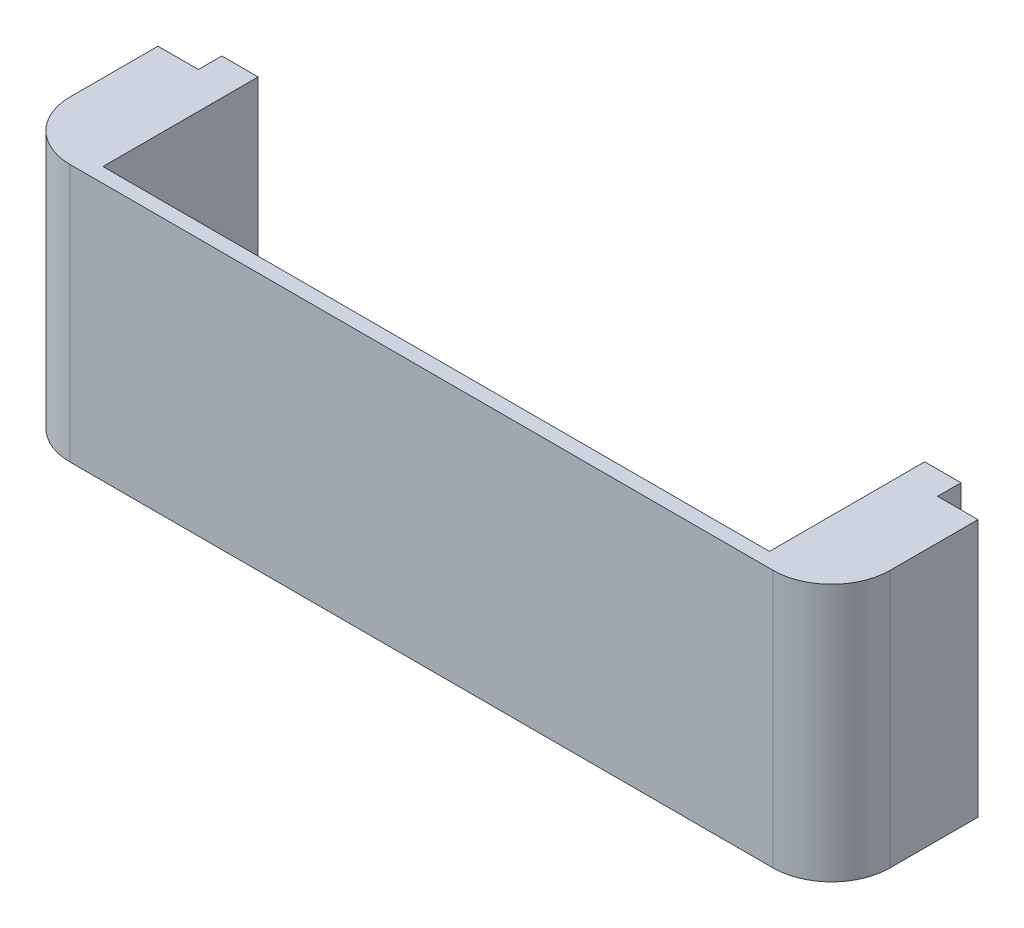
SolidWorks part; units mm, degrees
ref_plane "Front Plane" through (0, 0, 0) normal (0, 0, 1) x (1, 0, 0)
ref_plane "Top Plane" through (0, 0, 0) normal (0, 1, 0) x (1, 0, 0)
ref_plane "Right Plane" through (0, 0, 0) normal (1, 0, 0) x (0, 0, -1)
other "Configuration Table"
sketch "草图1" plane through (0, 0, 0) normal (0, 0, 1) x (1, 0, 0)
  line L0 (-15, 22) -> (-15, -22)
  line L1 (0, 22) -> (15, 22)
  line L2 (0, 22) -> (-15, 22)
  line L3 (15, 22) -> (15, -22)
  line L4 (15, -22) -> (-15, -22)
extrude "凸台-拉伸1" add sketch "草图1" along normal blind 14 contours L0 L4 L3 L1 L2
sketch "草图2" plane through (0, 22, 0) normal (0, 1, 0) x (1, 0, 0)
  line L3 (10, -4) -> (15, -14)
  line L4 (15, -14) -> (-15, -14)
  line L6 (-15, -14) -> (-10, -4)
  line L8 (3.1, -4) -> (3.1, 0)
  line L9 (-15, 0) -> (15, 0) construction
  line L10 (3.1, 0) -> (15, 0)
  line L11 (15, 0) -> (15, -14)
  line L12 (10, -4) -> (3.1, -4)
  line L13 (-3.1, -4) -> (-10, -4)
  line L14 (-15, -14) -> (-15, 0)
  line L15 (-15, 0) -> (-3.1, 0)
  line L16 (-3.1, 0) -> (-3.1, -4)
  line M14 (15, 0) -> (-15, 0)
  line M15 (-15, 0) -> (-15, -14)
  line M17 (15, -14) -> (15, 0)
extrude "切除-拉伸1" cut sketch "草图2" against normal blind 44 contours L16 L6 L13 M14 M15 | L12 L3 L8 M17 M14
sketch "草图3" plane through (0, 0, 0) normal (0, 0, -1) x (-1, 0, 0)
  line L2 (-3.1, 3.1) -> (-3.1, -3.1)
  line L4 (3.1, -22) -> (3.1, 22) construction
  line L5 (3.1, 3.1) -> (-3.1, 3.1)
  line L6 (-3.1, -22) -> (-3.1, 22) construction
  line L9 (-3.1, -3.1) -> (3.1, -3.1)
  line L10 (3.1, -22) -> (3.1, 22) construction
  line L11 (3.1, -3.1) -> (3.1, 3.1)
extrude "切除-拉伸2" cut sketch "草图3" against normal blind 4 contours L2 L9 L11 L5
sketch "草图4" plane through (0, 0, 14) normal (0, 0, 1) x (1, 0, 0)
  circle A0 centre (0, 0) radius 4
extrude "切除-拉伸3" cut sketch "草图4" against normal blind 5
sketch "草图5" plane through (0, 0, 9) normal (0, 0, 1) x (1, 0, 0)
  circle A0 centre (0, 0) radius 2.6
extrude "切除-拉伸4" cut sketch "草图5" against normal blind 5 contours A0
sketch "草图6" plane through (0, 0, 14) normal (0, 0, 1) x (1, 0, 0)
  circle A0 centre (0, 0) radius 4
extrude "凸台-拉伸2" add sketch "草图6" against normal blind 10
sketch "草图7" plane through (0, -22, 0) normal (0, -1, 0) x (-1, 0, 0)
  line L0 (-10, -4) -> (-3.1, -4) construction
  line L1 (3.1, 0) -> (-3.1, 0)
  line L2 (3.1, 0) -> (3.1, -4)
  line L3 (3.1, -4) -> (-3.1, -4)
  line L4 (-3.1, 0) -> (-3.1, -4)
  line L5 (-3.1, -4) -> (-3.1, 0) construction
extrude "凸台-拉伸3" add sketch "草图7" against normal blind 40
sketch "草图8" plane through (0, -22, 0) normal (0, -1, 0) x (1, 0, 0)
  line L0 (-10, 4) -> (-10, 14)
  line L1 (15, 14) -> (-15, 14) construction
  line L2 (-10, 14) -> (-15, 14)
  line L3 (-15, 14) -> (-10, 4)
  line L4 (10, 4) -> (10, 14)
  line L5 (10, 14) -> (15, 14)
  line L6 (15, 14) -> (10, 4)
  line M9 (10, 4) -> (15, 14)
  line M10 (15, 14) -> (-15, 14)
  line M11 (-15, 14) -> (-10, 4)
extrude "切除-拉伸5" cut sketch "草图8" against normal blind 50 contours L0 M11 M10 | L4 M9 M10
sketch "草图9" plane through (0, -22, 0) normal (0, -1, 0) x (1, 0, 0)
  line L0 (-10, 4) -> (-10, 29)
  line L5 (10, 4) -> (-10, 4)
  line L6 (10, 4) -> (10, 29)
  line L7 (-10, 29) -> (10, 29)
extrude "凸台-拉伸4" add sketch "草图9" against normal blind 44 contours L7 L6 L5 L0
sketch "草图10" plane through (0, -22, 0) normal (0, -1, 0) x (1, 0, 0)
  line L0 (-10, 29) -> (-10, 19)
  line L1 (-10, 4) -> (-10, 29) construction
  line L2 (0, 29) -> (-10, 29)
  arc A0 (-10, 19) -> (0, 29) centre (0, 19) cw
extrude "切除-拉伸6" cut sketch "草图10" against normal blind 44
sketch "草图11" plane through (0, -22, 0) normal (0, -1, 0) x (1, 0, 0)
  line L1 (120, 0) -> (123.1, 0)
  line L2 (116.9, 4) -> (110, 4)
  line L3 (123.1, 0) -> (123.1, 4)
  line L4 (123.1, 4) -> (130, 4)
  line L9 (116.9, 4) -> (116.9, 0)
  line L10 (116.9, 0) -> (120, 0)
  line L11 (10, 29) -> (110, 29)
  line L12 (10, 29) -> (10, 26.5)
  line L13 (10, 4) -> (10, 29) construction
  line L14 (10, 26.5) -> (110, 26.5)
  line L15 (110, 26.5) -> (110, 4)
  line L17 (110, 29) -> (120, 29)
  line L18 (130, 19) -> (130, 4)
  arc A0 (130, 19) -> (120, 29) centre (120, 19) ccw
extrude "凸台-拉伸5" add sketch "草图11" against normal blind 44 contours L17 A0 L18 L4 L3 L1 L10 L9 L2 L15 L14 L12 L11
sketch "草图12" plane through (0, 22, 0) normal (0, 1, 0) x (1, 0, 0)
  line L0 (3.1, -4) -> (10, -4)
  line L1 (10, -4) -> (10, -26.5)
  line L2 (10, -26.5) -> (3.1, -26.5)
  line L3 (3.1, -26.5) -> (3.1, -4)
  line L4 (116.9, -4) -> (110, -4)
  line L5 (110, -4) -> (110, -26.5)
  line L6 (110, -26.5) -> (116.9, -26.5)
  line L7 (116.9, -26.5) -> (116.9, -4)
extrude "切除-拉伸7" cut sketch "草图12" against normal blind 50 contours L3 L0 L1 L2 | L7 L4 L5 L6
